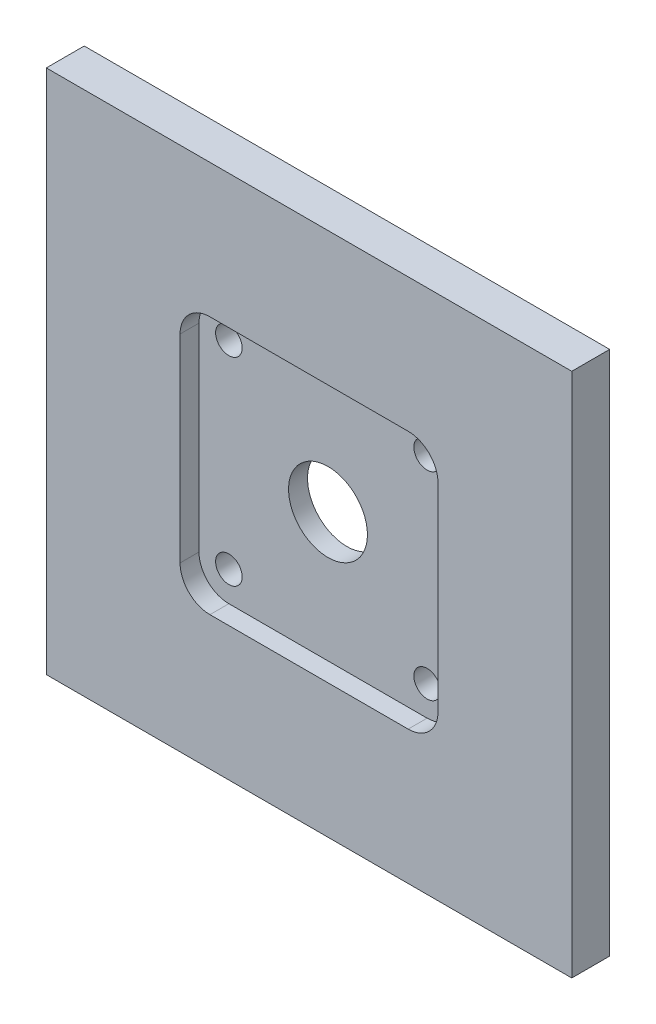
SolidWorks part; units mm, degrees
ref_plane "Front Plane" through (0, 0, 0) normal (0, 0, 1) x (1, 0, 0)
ref_plane "Top Plane" through (0, 0, 0) normal (0, 1, 0) x (1, 0, 0)
ref_plane "Right Plane" through (0, 0, 0) normal (1, 0, 0) x (0, 0, -1)
sketch "Sketch2" plane through (0, 0, 0) normal (0, 0, 1) x (1, 0, 0)
  line L0 (0, 0) -> (0, 110) construction
  line L1 (-110, 110) -> (110, 110)
  line L2 (-110, 110) -> (-110, -110)
  line L3 (-110, -110) -> (110, -110)
  line L4 (110, -110) -> (110, 110)
  point P5 (-110, 0)
  dimension "D1" = 110
  dimension "D2" = 110
  dimension "D3" = 110
extrude "Boss-Extrude1" add sketch "Sketch2" along normal blind 15.875
sketch "Sketch4" plane through (0, 0, 15.875) normal (0, 0, 1) x (1, 0, 0)
  line L0 (0, 0) -> (0, 53.5) construction
  line L1 (0, 0) -> (0, -54) construction
  line L4 (54, 54) -> (54, -54)
  line L5 (54, -54) -> (-54, -54)
  line L6 (-54, -54) -> (-54, 54)
  line L7 (-54, 54) -> (54, 54)
  point P6 (0, 54)
  point P9 (-54, 0)
  dimension "D3" = 108
  dimension "D4" = 108
extrude "Cut-Extrude1" cut sketch "Sketch4" against normal blind 7.9375 contours L7 L4 L5 L6
fillet "Fillet1" radius 12.5 4 edges at (-54, -54, 11.9062) (54, -54, 11.9062) (-54, 54, 11.9062) (54, 54, 11.9062)
sketch "Sketch5" plane through (0, 0, 7.9375) normal (0, 0, 1) x (1, 0, 0)
  line L0 (-50.3388, 50.3388) -> (-41.5, 41.5) construction
  arc A0 (-41.5, 54) -> (-54, 41.5) centre (-41.5, 41.5) ccw construction
  circle A1 centre (-41.5, 41.5) radius 5.5562
  dimension "D1" = 11.1125
extrude "Cut-Extrude2" cut sketch "Sketch5" against normal through all
mirror "Mirror1" about plane through (0, 0, 0) normal (0, 1, 0) of "Cut-Extrude2" second plane through (0, 0, 0) second plane normal (1, 0, 0)
sketch "Sketch6" plane through (0, 0, 7.9375) normal (0, 0, 1) x (1, 0, 0)
  circle A0 centre (0, 0) radius 16.51
  dimension "D1" = 33.02
extrude "Cut-Extrude3" cut sketch "Sketch6" against normal through all
